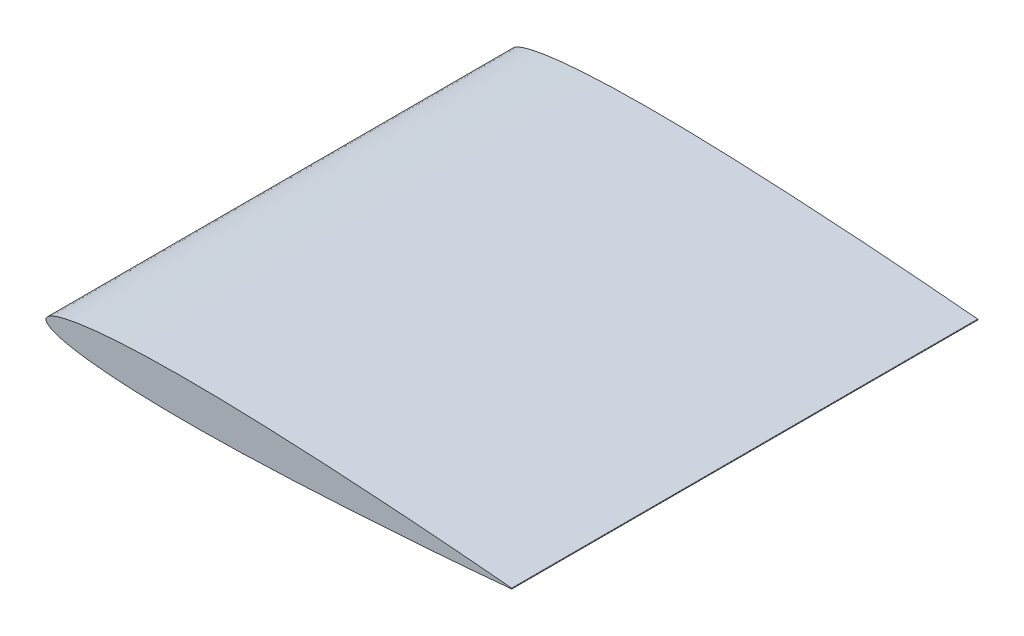
SolidWorks part; units mm, degrees
ref_plane "Front Plane" through (0, 0, 0) normal (0, 0, 1) x (1, 0, 0)
ref_plane "Top Plane" through (0, 0, 0) normal (0, 1, 0) x (1, 0, 0)
ref_plane "Right Plane" through (0, 0, 0) normal (1, 0, 0) x (0, 0, -1)
curve "Curve1"
  spline degree 3 poles (25.4, 0.0213, 0) (25.3979, 0.0215, 0) (25.3896, 0.0223, 0) (25.3708, 0.0241, 0) (25.3395, 0.027, 0) (25.2957, 0.0311, 0) (25.2395, 0.0363, 0) (25.1709, 0.0426, 0) (25.0901, 0.0501, 0) (24.997, 0.0587, 0) (24.8917, 0.0683, 0) (24.7744, 0.079, 0) (24.6452, 0.0907, 0) (24.5043, 0.1034, 0) (24.3517, 0.117, 0) (24.1875, 0.1315, 0) (24.0121, 0.147, 0) (23.8254, 0.1632, 0) (23.6278, 0.1803, 0) (23.4194, 0.1981, 0) (23.2005, 0.2167, 0) (22.9711, 0.2359, 0) (22.7317, 0.2558, 0) (22.4823, 0.2763, 0) (22.2233, 0.2973, 0) (21.9549, 0.3188, 0) (21.6773, 0.3408, 0) (21.3909, 0.3631, 0) (21.0959, 0.3859, 0) (20.7926, 0.4089, 0) (20.4814, 0.4323, 0) (20.1624, 0.4558, 0) (19.8361, 0.4795, 0) (19.5028, 0.5034, 0) (19.1627, 0.5274, 0) (18.8163, 0.5513, 0) (18.4638, 0.5753, 0) (18.1056, 0.5992, 0) (17.7421, 0.6229, 0) (17.3737, 0.6466, 0) (17.0006, 0.6699, 0) (16.6232, 0.693, 0) (16.242, 0.7158, 0) (15.8573, 0.7382, 0) (15.4695, 0.7601, 0) (15.079, 0.7816, 0) (14.6861, 0.8025, 0) (14.2912, 0.8228, 0) (13.8948, 0.8424, 0) (13.4972, 0.8613, 0) (13.0988, 0.8794, 0) (12.7, 0.8966, 0) (12.3012, 0.9129, 0) (11.9028, 0.9283, 0) (11.5052, 0.9426, 0) (11.1088, 0.9558, 0) (10.7139, 0.9679, 0) (10.3211, 0.9787, 0) (9.9305, 0.9884, 0) (9.5427, 0.9966, 0) (9.158, 1.0035, 0) (8.7768, 1.009, 0) (8.3995, 1.0131, 0) (8.0264, 1.0156, 0) (7.6579, 1.0165, 0) (7.2944, 1.016, 0) (6.9362, 1.0137, 0) (6.5837, 1.0099, 0) (6.2373, 1.0044, 0) (5.8972, 0.9972, 0) (5.5639, 0.9883, 0) (5.2375, 0.9777, 0) (4.9186, 0.9655, 0) (4.6073, 0.9514, 0) (4.304, 0.9358, 0) (4.009, 0.9184, 0) (3.7226, 0.8995, 0) (3.4451, 0.8788, 0) (3.1766, 0.8566, 0) (2.9176, 0.8328, 0) (2.6682, 0.8075, 0) (2.4287, 0.7806, 0) (2.1994, 0.7523, 0) (1.9804, 0.7226, 0) (1.7719, 0.6915, 0) (1.5743, 0.6591, 0) (1.3876, 0.6255, 0) (1.2121, 0.5906, 0) (1.0479, 0.5546, 0) (0.8952, 0.5175, 0) (0.7542, 0.4794, 0) (0.6249, 0.4403, 0) (0.5074, 0.4002, 0) (0.402, 0.3593, 0) (0.3086, 0.3175, 0) (0.2274, 0.275, 0) (0.1583, 0.2316, 0) (0.1014, 0.1873, 0) (0.0567, 0.1422, 0) (0.0243, 0.096, 0) (0.0045, 0.0485, 0) (-0.0022, 0, 0) (0.0045, -0.0485, 0) (0.0243, -0.096, 0) (0.0567, -0.1422, 0) (0.1014, -0.1873, 0) (0.1583, -0.2316, 0) (0.2274, -0.275, 0) (0.3086, -0.3175, 0) (0.402, -0.3593, 0) (0.5074, -0.4002, 0) (0.6249, -0.4403, 0) (0.7542, -0.4794, 0) (0.8952, -0.5175, 0) (1.0479, -0.5546, 0) (1.2121, -0.5906, 0) (1.3876, -0.6255, 0) (1.5743, -0.6591, 0) (1.7719, -0.6915, 0) (1.9804, -0.7226, 0) (2.1994, -0.7523, 0) (2.4287, -0.7806, 0) (2.6682, -0.8075, 0) (2.9176, -0.8328, 0) (3.1766, -0.8566, 0) (3.4451, -0.8788, 0) (3.7226, -0.8995, 0) (4.009, -0.9184, 0) (4.304, -0.9358, 0) (4.6073, -0.9514, 0) (4.9186, -0.9655, 0) (5.2375, -0.9777, 0) (5.5639, -0.9883, 0) (5.8972, -0.9972, 0) (6.2373, -1.0044, 0) (6.5837, -1.0099, 0) (6.9362, -1.0137, 0) (7.2944, -1.016, 0) (7.6579, -1.0165, 0) (8.0264, -1.0156, 0) (8.3995, -1.0131, 0) (8.7768, -1.009, 0) (9.158, -1.0035, 0) (9.5427, -0.9966, 0) (9.9305, -0.9884, 0) (10.3211, -0.9787, 0) (10.7139, -0.9679, 0) (11.1088, -0.9558, 0) (11.5052, -0.9426, 0) (11.9028, -0.9283, 0) (12.3012, -0.9129, 0) (12.7, -0.8966, 0) (13.0988, -0.8794, 0) (13.4972, -0.8613, 0) (13.8948, -0.8424, 0) (14.2912, -0.8228, 0) (14.6861, -0.8025, 0) (15.079, -0.7816, 0) (15.4695, -0.7601, 0) (15.8573, -0.7382, 0) (16.242, -0.7158, 0) (16.6232, -0.693, 0) (17.0006, -0.6699, 0) (17.3737, -0.6466, 0) (17.7421, -0.6229, 0) (18.1056, -0.5992, 0) (18.4638, -0.5753, 0) (18.8163, -0.5513, 0) (19.1627, -0.5274, 0) (19.5028, -0.5034, 0) (19.8361, -0.4795, 0) (20.1624, -0.4558, 0) (20.4814, -0.4323, 0) (20.7926, -0.4089, 0) (21.0959, -0.3859, 0) (21.3909, -0.3631, 0) (21.6773, -0.3408, 0) (21.9549, -0.3188, 0) (22.2233, -0.2973, 0) (22.4823, -0.2763, 0) (22.7317, -0.2558, 0) (22.9711, -0.2359, 0) (23.2005, -0.2167, 0) (23.4194, -0.1981, 0) (23.6278, -0.1803, 0) (23.8254, -0.1632, 0) (24.0121, -0.147, 0) (24.1875, -0.1315, 0) (24.3517, -0.117, 0) (24.5043, -0.1034, 0) (24.6452, -0.0907, 0) (24.7744, -0.079, 0) (24.8917, -0.0683, 0) (24.997, -0.0587, 0) (25.0901, -0.0501, 0) (25.1709, -0.0426, 0) (25.2395, -0.0363, 0) (25.2957, -0.0311, 0) (25.3395, -0.027, 0) (25.3708, -0.0241, 0) (25.3896, -0.0223, 0) (25.3979, -0.0215, 0) (25.4, -0.0213, 0) knots 0 0 0 0 0.000123 0.000491 0.001103 0.00196 0.003061 0.004403 0.005987 0.00781 0.00987 0.012166 0.014695 0.017455 0.020443 0.023655 0.027089 0.030742 0.034609 0.038686 0.042971 0.047458 0.052143 0.057021 0.062088 0.067338 0.072766 0.078367 0.084136 0.090066 0.096151 0.102387 0.108765 0.115282 0.121928 0.128698 0.135587 0.142585 0.149687 0.156886 0.164174 0.171545 0.17899 0.186504 0.194077 0.201703 0.209374 0.217082 0.224821 0.232582 0.240357 0.248139 0.255921 0.263694 0.271451 0.279184 0.286886 0.29455 0.302166 0.309729 0.317231 0.324663 0.332021 0.339295 0.346479 0.353566 0.360549 0.367422 0.374177 0.380809 0.387311 0.393676 0.399899 0.405973 0.411894 0.417656 0.423252 0.428678 0.43393 0.439001 0.443888 0.448586 0.453092 0.4574 0.461508 0.465412 0.46911 0.472598 0.475875 0.478937 0.481785 0.484418 0.486835 0.489038 0.491029 0.492814 0.494398 0.495793 0.497018 0.498099 0.499075 0.5 0.500925 0.501901 0.502982 0.504207 0.505602 0.507186 0.508971 0.510962 0.513165 0.515582 0.518215 0.521063 0.524125 0.527402 0.53089 0.534588 0.538492 0.5426 0.546908 0.551414 0.556112 0.560999 0.56607 0.571322 0.576748 0.582344 0.588106 0.594027 0.600101 0.606324 0.612689 0.619191 0.625823 0.632578 0.639451 0.646434 0.653521 0.660705 0.667979 0.675337 0.682769 0.690271 0.697834 0.70545 0.713114 0.720816 0.728549 0.736306 0.744079 0.751861 0.759643 0.767418 0.775179 0.782918 0.790626 0.798297 0.805923 0.813496 0.82101 0.828455 0.835826 0.843114 0.850313 0.857415 0.864413 0.871302 0.878072 0.884718 0.891235 0.897613 0.903849 0.909934 0.915864 0.921633 0.927234 0.932662 0.937912 0.942979 0.947857 0.952542 0.957029 0.961314 0.965391 0.969258 0.972911 0.976345 0.979557 0.982545 0.985305 0.987834 0.99013 0.99219 0.994013 0.995597 0.996939 0.99804 0.998897 0.999509 0.999877 1 1 1 1
sketch "Sketch1" plane through (0, 0, 0) normal (0, 0, 1) x (1, 0, 0)
  line L0 (-47.625, 0) -> (142.875, 0) construction
  line L1 (-47.625, 0) -> (-47.625, 14.5268) construction
  line L2 (142.368, 0) -> (-48.132, 0) construction
  arc A0 (142.7294, 0.16) -> (142.7292, -0.1598) centre (142.7144, 0.0001) cw
  spline S1 degree 3 poles (142.7294, 0.16) (142.4792, 0.1834) (142.0886, 0.2201) (141.5267, 0.2727) (141.0128, 0.3205) (140.4067, 0.3768) (139.709, 0.4412) (138.9203, 0.514) (138.0414, 0.5943) (137.0732, 0.6822) (136.0168, 0.7781) (134.873, 0.8805) (133.643, 0.9902) (132.3281, 1.1065) (130.9295, 1.2292) (129.4486, 1.3577) (127.887, 1.4924) (126.246, 1.6323) (124.5273, 1.7771) (122.7328, 1.9271) (120.8641, 2.0814) (118.9229, 2.2396) (116.9113, 2.4021) (114.8313, 2.5676) (112.6849, 2.7363) (110.4742, 2.908) (108.2014, 3.0818) (105.8688, 3.2578) (103.4787, 3.4357) (101.0332, 3.6145) (98.535, 3.7947) (95.9866, 3.9754) (93.3903, 4.1562) (90.7488, 4.3373) (88.0647, 4.5174) (85.3405, 4.6969) (82.5791, 4.8753) (79.7831, 5.0516) (76.9554, 5.2263) (74.0986, 5.3984) (71.2156, 5.5677) (67.3276, 5.7895) (63.4141, 6.0034) (59.4788, 6.2072) (56.5079, 6.3559) (53.5281, 6.4987) (50.5425, 6.6357) (47.554, 6.7666) (44.5654, 6.8902) (41.5798, 7.0066) (38.6, 7.1156) (35.629, 7.216) (32.6698, 7.308) (29.7253, 7.3906) (26.7984, 7.4643) (23.892, 7.5274) (21.009, 7.5809) (18.1521, 7.6231) (15.3243, 7.6551) (12.5282, 7.6751) (8.8716, 7.6867) (5.2665, 7.675) (1.7165, 7.6377) (-0.8799, 7.5977) (-3.4286, 7.545) (-5.9269, 7.4799) (-8.3725, 7.4016) (-10.7629, 7.311) (-13.0957, 7.2072) (-15.3687, 7.091) (-17.5796, 6.9621) (-19.7262, 6.8209) (-22.4547, 6.6193) (-25.0901, 6.3919) (-27.6288, 6.1353) (-29.4237, 5.9346) (-31.1426, 5.7237) (-32.784, 5.5015) (-34.3461, 5.2696) (-35.8274, 5.0276) (-37.2265, 4.7762) (-38.542, 4.5157) (-39.7726, 4.2464) (-40.917, 3.969) (-41.9745, 3.6841) (-42.9437, 3.3912) (-43.8239, 3.0914) (-44.6144, 2.7853) (-45.3142, 2.4722) (-45.9234, 2.1535) (-46.4412, 1.8285) (-46.8677, 1.4973) (-47.2031, 1.1595) (-47.446, 0.813) (-47.5947, 0.457) (-47.6445, 0.0937) (-47.5951, -0.2696) (-47.4467, -0.6258) (-47.2042, -0.9725) (-46.8691, -1.3107) (-46.4429, -1.6422) (-45.9254, -1.9678) (-45.3166, -2.2871) (-44.617, -2.6009) (-43.8269, -2.9078) (-42.9469, -3.2084) (-41.978, -3.5022) (-40.9209, -3.7882) (-39.7767, -4.0667) (-38.5463, -4.3373) (-37.2311, -4.599) (-35.8322, -4.8518) (-34.3512, -5.0952) (-32.7893, -5.3287) (-31.1482, -5.5525) (-29.4294, -5.7651) (-27.6348, -5.9675) (-25.0963, -6.2267) (-22.4611, -6.4567) (-19.7328, -6.661) (-17.5863, -6.8042) (-15.3756, -6.9353) (-13.1027, -7.0538) (-10.77, -7.1599) (-8.3797, -7.2528) (-5.9342, -7.3336) (-3.4359, -7.4011) (-0.8873, -7.4563) (1.709, -7.4989) (5.259, -7.5396) (8.8641, -7.5549) (12.5207, -7.5468) (15.3168, -7.5296) (18.1447, -7.5004) (21.0016, -7.461) (23.8847, -7.4104) (26.7911, -7.3501) (29.7181, -7.2793) (32.6627, -7.1996) (35.622, -7.1105) (38.593, -7.013) (41.5729, -6.907) (44.5587, -6.7935) (47.5473, -6.6728) (50.536, -6.5449) (53.5218, -6.4108) (56.5017, -6.271) (59.4727, -6.1251) (63.4082, -5.9253) (67.322, -5.7152) (71.2102, -5.4972) (74.0933, -5.3307) (76.9503, -5.1614) (79.7782, -4.9896) (82.5744, -4.816) (85.336, -4.6403) (88.0602, -4.4635) (90.7446, -4.286) (93.3862, -4.1075) (95.9827, -3.9293) (98.5313, -3.751) (101.0297, -3.5733) (103.4753, -3.3969) (105.8656, -3.2214) (108.1984, -3.0477) (110.4714, -2.8761) (112.6822, -2.7066) (114.8287, -2.54) (116.9089, -2.3765) (118.9207, -2.216) (120.862, -2.0597) (122.7309, -1.9073) (124.5256, -1.759) (126.2444, -1.6159) (127.8855, -1.4776) (129.4473, -1.3445) (130.9283, -1.2175) (132.327, -1.0962) (133.6421, -0.9811) (134.8721, -0.8726) (136.016, -0.7714) (137.0726, -0.6765) (138.0408, -0.5895) (138.9198, -0.5101) (139.7086, -0.4381) (140.4064, -0.3744) (141.0125, -0.3187) (141.714, -0.2542) (142.276, -0.2019) (142.6666, -0.1656) (142.7292, -0.1598) knots 0 0 0 0 0.00196 0.003061 0.004403 0.005987 0.00781 0.00987 0.012166 0.014695 0.017455 0.020443 0.023655 0.027089 0.030742 0.034609 0.038686 0.042971 0.047458 0.052143 0.057021 0.062088 0.067338 0.072766 0.078367 0.084136 0.090066 0.096151 0.102387 0.108765 0.115282 0.121928 0.128698 0.135587 0.142585 0.149687 0.156886 0.164174 0.171545 0.17899 0.186504 0.194077 0.209374 0.217082 0.224821 0.232582 0.240357 0.248139 0.255921 0.263694 0.271451 0.279184 0.286886 0.29455 0.302166 0.309729 0.317231 0.324663 0.332021 0.339295 0.346479 0.360549 0.367422 0.374177 0.380809 0.387311 0.393676 0.399899 0.405973 0.411894 0.417656 0.423252 0.428678 0.439001 0.443888 0.448586 0.453092 0.4574 0.461508 0.465412 0.46911 0.472598 0.475875 0.478937 0.481785 0.484418 0.486835 0.489038 0.491029 0.492814 0.494398 0.495793 0.497018 0.498099 0.499075 0.5 0.500925 0.501901 0.502982 0.504207 0.505602 0.507186 0.508971 0.510962 0.513165 0.515582 0.518215 0.521063 0.524125 0.527402 0.53089 0.534588 0.538492 0.5426 0.546908 0.551414 0.556112 0.560999 0.571322 0.576748 0.582344 0.588106 0.594027 0.600101 0.606324 0.612689 0.619191 0.625823 0.632578 0.639451 0.653521 0.660705 0.667979 0.675337 0.682769 0.690271 0.697834 0.70545 0.713114 0.720816 0.728549 0.736306 0.744079 0.751861 0.759643 0.767418 0.775179 0.782918 0.790626 0.805923 0.813496 0.82101 0.828455 0.835826 0.843114 0.850313 0.857415 0.864413 0.871302 0.878072 0.884718 0.891235 0.897613 0.903849 0.909934 0.915864 0.921633 0.927234 0.932662 0.937912 0.942979 0.947857 0.952542 0.957029 0.961314 0.965391 0.969258 0.972911 0.976345 0.979557 0.982545 0.985305 0.987834 0.99013 0.99219 0.994013 0.995597 0.996939 0.999509 1 1 1 1
  point P7 (0, 0)
  point P8 (0, 0)
  dimension "D1" = 190.5
  dimension "D2" = 47.625
  dimension "D3" = 0
extrude "Boss-Extrude1" add sketch "Sketch1" against normal blind 190.5
